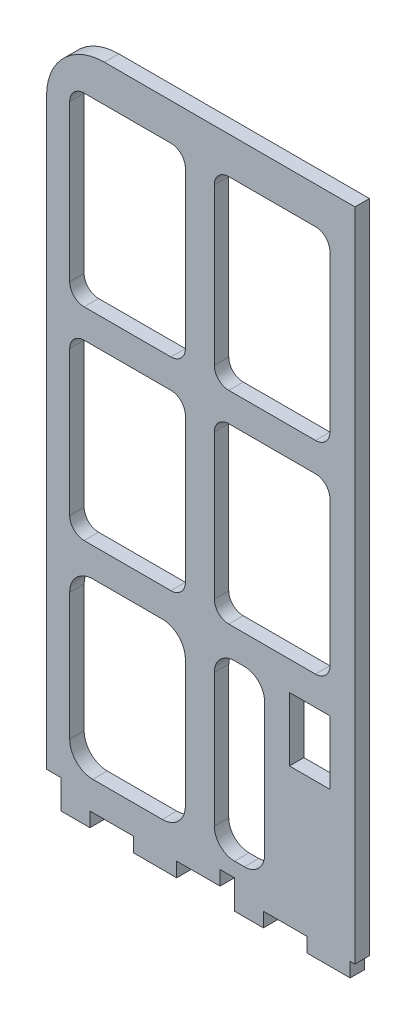
SolidWorks part; units mm, degrees
material "Balsa"
ref_plane "Front Plane" through (0, 0, 0) normal (0, 0, 1) x (1, 0, 0)
ref_plane "Top Plane" through (0, 0, 0) normal (0, 1, 0) x (1, 0, 0)
ref_plane "Right Plane" through (0, 0, 0) normal (1, 0, 0) x (0, 0, -1)
sketch "Sketch1" plane through (0, 0, 0) normal (0, 0, 1) x (1, 0, 0)
  line L1 (135.4577, 0) -> (135.4577, 287.9852)
  line L2 (135.4577, 287.9852) -> (25.4, 287.9852)
  line L4 (0, 0) -> (0, -6.35)
  line L6 (0, 0) -> (0, -6.35)
  line L7 (0, -6.35) -> (19.05, -6.35)
  line L8 (19.05, 0) -> (19.05, -6.35)
  line L10 (38.1, 0) -> (38.1, -6.35)
  line L11 (38.1, -6.35) -> (57.15, -6.35)
  line L12 (57.15, 0) -> (57.15, -6.35)
  line L14 (76.2, 0) -> (76.2, -6.35)
  line L15 (76.2, -6.35) -> (95.25, -6.35)
  line L16 (95.25, 0) -> (95.25, -6.35)
  line L18 (114.3, 0) -> (114.3, -6.35)
  line L19 (114.3, -6.35) -> (133.35, -6.35)
  line L20 (133.35, 0) -> (133.35, -6.35)
  line L25 (19.05, 0) -> (38.1, 0)
  line L26 (57.15, 0) -> (76.2, 0)
  line L27 (95.25, 0) -> (114.3, 0)
  line L28 (133.35, 0) -> (135.4577, 0)
  line L30 (0, 262.5852) -> (0, 0)
  line L31 (25.4, 287.9852) -> (135.4577, 287.9852)
  line L32 (19.05, 0) -> (38.1, 0)
  line L33 (38.1, -6.35) -> (57.15, -6.35)
  line L34 (57.15, 0) -> (76.2, 0)
  arc A0 (25.4, 287.9852) -> (0, 262.5852) centre (25.4, 262.5852) ccw
  point P8 (0, 287.9852)
  point P11 (135.4577, 287.9852)
  dimension "D4" = 6.35
  dimension "D5" = 19.05
  dimension "D1" = 135.4577
  dimension "D2" = 287.9852
  dimension "D3" = 135.4577
  dimension "D6" = 6.35
  dimension "D7" = 19.05
  dimension "D8" = 19.05
  dimension "D9" = 19.05
  dimension "D10" = 19.05
  dimension "D11" = 6.35
  dimension "D12" = 19.05
  dimension "D13" = 19.05
  dimension "D14" = 6.35
  dimension "D15" = 6.35
  dimension "D16" = 0
  dimension "D17" = 262.5852
  dimension "D21" = 6.35
  dimension "D22" = 6.35
  dimension "D23" = 6.35
extrude "Boss-Extrude1" add sketch "Sketch1" along normal blind 6.35
sketch "Sketch2" plane through (0, 0, 6.35) normal (0, 0, 1) x (1, 0, 0)
  line L38 (73.66, 22.86) -> (73.66, 78.74)
  line L39 (20.32, 12.7) -> (50.8, 12.7)
  line L40 (73.66, 196.85) -> (73.66, 265.43)
  line L41 (80.01, 190.5) -> (118.11, 190.5)
  line L42 (124.46, 196.85) -> (124.46, 265.43)
  line L43 (80.01, 271.78) -> (118.11, 271.78)
  line L45 (10.16, 196.85) -> (10.16, 265.43)
  line L46 (16.51, 190.5) -> (54.61, 190.5)
  line L47 (60.96, 196.85) -> (60.96, 265.43)
  line L48 (16.51, 271.78) -> (54.61, 271.78)
  line L49 (73.66, 107.95) -> (73.66, 171.45)
  line L50 (80.01, 101.6) -> (118.11, 101.6)
  line L51 (124.46, 107.95) -> (124.46, 171.45)
  line L52 (80.01, 177.8) -> (118.11, 177.8)
  line L53 (10.16, 107.95) -> (10.16, 171.45)
  line L54 (16.51, 101.6) -> (54.61, 101.6)
  line L55 (60.96, 107.95) -> (60.96, 171.45)
  line L56 (16.51, 177.8) -> (54.61, 177.8)
  line L68 (10.16, 22.86) -> (10.16, 78.74)
  line L69 (20.32, 88.9) -> (50.8, 88.9)
  line L70 (60.96, 22.86) -> (60.96, 78.74)
  line L71 (83.82, 12.7) -> (114.3, 12.7)
  line L72 (124.46, 22.86) -> (124.46, 78.74)
  line L73 (83.82, 88.9) -> (114.3, 88.9)
  line L104 (19.05, -38.1) -> (44.45, -38.1) [skipped]
  line L105 (137.16, 19.05) -> (137.16, 82.55) [skipped]
  line L106 (146.05, 12.7) -> (171.45, 12.7) [skipped]
  line L107 (187.96, 19.05) -> (187.96, 82.55) [skipped]
  line L108 (146.05, 88.9) -> (171.45, 88.9) [skipped]
  line L109 (137.16, -44.45) -> (137.16, 19.05) [skipped]
  line L110 (146.05, -50.8) -> (171.45, -50.8) [skipped]
  line L111 (187.96, -44.45) -> (187.96, 19.05) [skipped]
  line L112 (146.05, 25.4) -> (171.45, 25.4) [skipped]
  line L113 (137.16, -103.373) -> (137.16, -49.027) [skipped]
  line L114 (150.627, -114.3) -> (166.873, -114.3) [skipped]
  line L115 (187.96, -103.373) -> (187.96, -49.027) [skipped]
  line L116 (150.627, -38.1) -> (166.873, -38.1) [skipped]
  line L117 (73.66, -97.4702) -> (73.66, -54.9298) [skipped]
  line L118 (124.46, -97.4702) -> (124.46, -54.9298) [skipped]
  line L119 (93.0298, -114.3) -> (97.4702, -114.3) [skipped]
  line L120 (93.0298, -38.1) -> (97.4702, -38.1) [skipped]
  line L121 (10.16, -105.3232) -> (10.16, -47.0768) [skipped]
  line L122 (37.2067, -114.3) -> (48.1202, -114.3) [skipped]
  line L123 (60.96, -105.3232) -> (60.96, -58.7589) [skipped]
  line L124 (19.05, 25.4) -> (44.45, 25.4) [skipped]
  line L125 (60.96, -50.8) -> (60.96, 25.4) [skipped]
  line L126 (19.05, -50.8) -> (44.45, -50.8) [skipped]
  line L127 (10.16, -50.8) -> (10.16, 25.4) [skipped]
  line L128 (124.46, -69.3053) -> (124.46, 6.8947) [skipped]
  line L129 (73.66, -50.8) -> (73.66, 25.4) [skipped]
  line L130 (94.7053, 25.4) -> (103.4599, 25.4) [skipped]
  line L131 (94.7053, -50.8) -> (103.4599, -50.8) [skipped]
  arc A24 (73.66, 78.74) -> (83.82, 88.9) centre (83.82, 78.74) cw
  arc A25 (124.46, 78.74) -> (114.3, 88.9) centre (114.3, 78.74) ccw
  arc A26 (114.3, 12.7) -> (124.46, 22.86) centre (114.3, 22.86) ccw
  arc A27 (73.66, 22.86) -> (83.82, 12.7) centre (83.82, 22.86) ccw
  arc A28 (50.8, 12.7) -> (60.96, 22.86) centre (50.8, 22.86) ccw
  arc A29 (50.8, 88.9) -> (60.96, 78.74) centre (50.8, 78.74) cw
  arc A30 (10.16, 78.74) -> (20.32, 88.9) centre (20.32, 78.74) cw
  arc A31 (20.32, 12.7) -> (10.16, 22.86) centre (20.32, 22.86) cw
  arc A57 (10.16, 196.85) -> (16.51, 190.5) centre (16.51, 196.85) ccw
  arc A58 (10.16, 265.43) -> (16.51, 271.78) centre (16.51, 265.43) cw
  arc A59 (60.96, 265.43) -> (54.61, 271.78) centre (54.61, 265.43) ccw
  arc A60 (54.61, 190.5) -> (60.96, 196.85) centre (54.61, 196.85) ccw
  arc A61 (73.66, 196.85) -> (80.01, 190.5) centre (80.01, 196.85) ccw
  arc A62 (73.66, 265.43) -> (80.01, 271.78) centre (80.01, 265.43) cw
  arc A63 (124.46, 265.43) -> (118.11, 271.78) centre (118.11, 265.43) ccw
  arc A64 (118.11, 190.5) -> (124.46, 196.85) centre (118.11, 196.85) ccw
  arc A65 (10.16, 107.95) -> (16.51, 101.6) centre (16.51, 107.95) ccw
  arc A66 (10.16, 171.45) -> (16.51, 177.8) centre (16.51, 171.45) cw
  arc A67 (60.96, 171.45) -> (54.61, 177.8) centre (54.61, 171.45) ccw
  arc A68 (54.61, 101.6) -> (60.96, 107.95) centre (54.61, 107.95) ccw
  arc A69 (73.66, 107.95) -> (80.01, 101.6) centre (80.01, 107.95) ccw
  arc A70 (73.66, 171.45) -> (80.01, 177.8) centre (80.01, 171.45) cw
  arc A71 (124.46, 171.45) -> (118.11, 177.8) centre (118.11, 171.45) ccw
  arc A72 (118.11, 101.6) -> (124.46, 107.95) centre (118.11, 107.95) ccw
  point P88 (60.96, 12.7)
  point P93 (10.16, 88.9)
  point P96 (10.16, 12.7)
  dimension "D7" = 81.28
  dimension "D12" = 76.2
  dimension "D11" = 50.8
  dimension "D1" = 76.2
  dimension "D2" = 50.8
  dimension "D3" = 3
  dimension "D4" = 3
  dimension "D5" = 10.16
  dimension "D6" = 12.7
  dimension "D8" = 12.7
  dimension "D9" = 81.28
  dimension "D10" = 50.8
  dimension "D13" = 76.2
  dimension "D14" = 50.8
  dimension "D15" = 50.8
  dimension "D16" = 12.7
  dimension "D17" = 12.7
  dimension "D18" = 0
  dimension "D19" = 0
  dimension "D20" = 12.7
  dimension "D21" = 12.7
  dimension "D22" = 12.7
  dimension "D23" = 12.7
extrude "Cut-Extrude1" cut sketch "Sketch2" against normal through all
sketch "Sketch3" plane through (0, 0, 6.35) normal (0, 0, 1) x (1, 0, 0)
  line L1 (0, -6.35) -> (6.35, -6.35)
  line L2 (0, -6.35) -> (0, 6.35)
  line L3 (0, 6.35) -> (6.35, 6.35)
  line L4 (6.35, -6.35) -> (6.35, 6.35)
  line L5 (76.2, -6.35) -> (82.55, -6.35)
  line L6 (76.2, -6.35) -> (76.2, 6.35)
  line L7 (76.2, 6.35) -> (82.55, 6.35)
  line L8 (82.55, -6.35) -> (82.55, 6.35)
  dimension "D1" = 6.35
  dimension "D2" = 12.7
  dimension "D3" = 6.35
  dimension "D4" = 12.7
extrude "Cut-Extrude2" cut sketch "Sketch3" against normal through all
sketch "Sketch4" plane through (0, 0, 6.35) normal (0, 0, 1) x (1, 0, 0)
  line L5 (69.1558, 89.874) -> (128.0503, 89.874)
  line L6 (69.1558, 89.874) -> (69.1558, 9.4409)
  line L7 (69.1558, 9.4409) -> (128.0503, 9.4409)
  line L8 (128.0503, 89.874) -> (128.0503, 9.4409)
  dimension "D1" = 80.433
extrude "Boss-Extrude3" add sketch "Sketch4" against normal up to surface (6.35 mm away) from surface at 0 contours L8 L7 L6 L5 up to face at (99.06, 50.8, 0) starting at face at (66.7676, 35.5833, 6.35)
ref_plane "Plane1" through (50.8, 88.9, 0) normal (-1, 0, 0) x (0, 0, 1)
sketch "Sketch6" plane through (0, 0, 0) normal (0, 0, -1) x (-1, 0, 0)
  line L1 (-124.46, 88.9) -> (-106.68, 88.9)
  line L2 (-124.46, 88.9) -> (-124.46, 60.96)
  line L3 (-124.46, 60.96) -> (-106.68, 60.96)
  line L4 (-106.68, 88.9) -> (-106.68, 60.96)
  dimension "D1" = 17.78
  dimension "D2" = 27.94
extrude "Cut-Extrude3" cut sketch "Sketch6" against normal through all
sketch "Sketch7" plane through (0, 0, 6.35) normal (0, 0, 1) x (1, 0, 0)
  line L0 (50.8, 88.9) -> (20.32, 88.9) construction
  line L1 (82.55, 88.9) -> (86.868, 88.9)
  line L2 (73.66, 80.01) -> (73.66, 21.59)
  line L3 (82.55, 12.7) -> (86.868, 12.7)
  line L4 (95.758, 80.01) -> (95.758, 21.59)
  line L5 (73.66, 171.45) -> (73.66, 107.95) construction
  line L6 (20.32, 12.7) -> (50.8, 12.7) construction
  line L7 (106.68, 60.96) -> (106.68, 88.9) construction
  arc A0 (73.66, 21.59) -> (82.55, 12.7) centre (82.55, 21.59) ccw
  arc A1 (86.868, 12.7) -> (95.758, 21.59) centre (86.868, 21.59) ccw
  arc A2 (86.868, 88.9) -> (95.758, 80.01) centre (86.868, 80.01) cw
  arc A3 (82.55, 88.9) -> (73.66, 80.01) centre (82.55, 80.01) ccw
  dimension "D2" = 8.89
  dimension "D1" = 10.922
extrude "Cut-Extrude4" cut sketch "Sketch7" against normal up to surface (6.35 mm away) up to face at (115.57, 74.93, 0)
